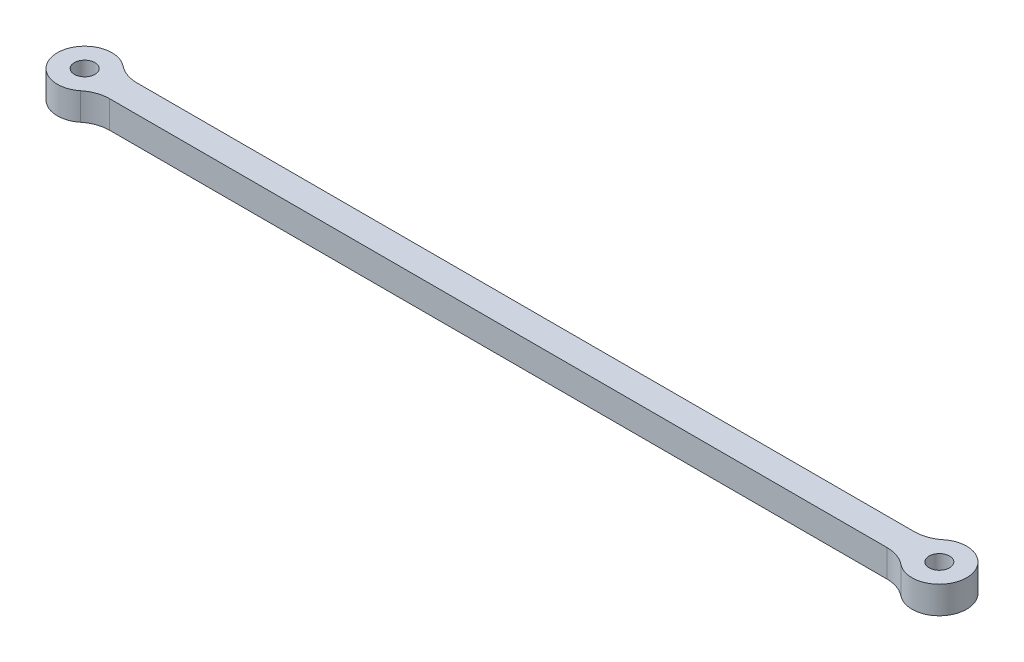
SolidWorks part; units mm, degrees
ref_plane "前视基准面" through (0, 0, 0) normal (0, 0, 1) x (1, 0, 0)
ref_plane "上视基准面" through (0, 0, 0) normal (0, 1, 0) x (1, 0, 0)
ref_plane "右视基准面" through (0, 0, 0) normal (1, 0, 0) x (0, 0, -1)
sketch "草图1" plane through (0, 0, 0) normal (0, 1, 0) x (1, 0, 0)
  line L0 (0, 0) -> (250, 0) construction
  line L1 (6.9282, 4) -> (243.0718, 4)
  line L2 (6.9282, -4) -> (243.0718, -4)
  arc A2 (243.0718, -4) -> (243.0718, 4) centre (250, 0) ccw
  arc A3 (6.9282, 4) -> (6.9282, -4) centre (0, 0) ccw
  circle A4 centre (0, 0) radius 3
  circle A5 centre (250, 0) radius 3
  point P3 (160, 0)
  dimension "D2" = 6
  dimension "D3" = 16
  dimension "D4" = 16
  dimension "D5" = 6
  dimension "D1" = 250
  dimension "D6" = 8
extrude "凸台-拉伸1" add sketch "草图1" along normal blind 8 contours A3 L2 A2 L1
fillet "圆角1" radius 10 4 edges at (243.0718, 4, 4) (243.0718, 4, -4) (6.9282, 4, -4) (6.9282, 4, 4)
